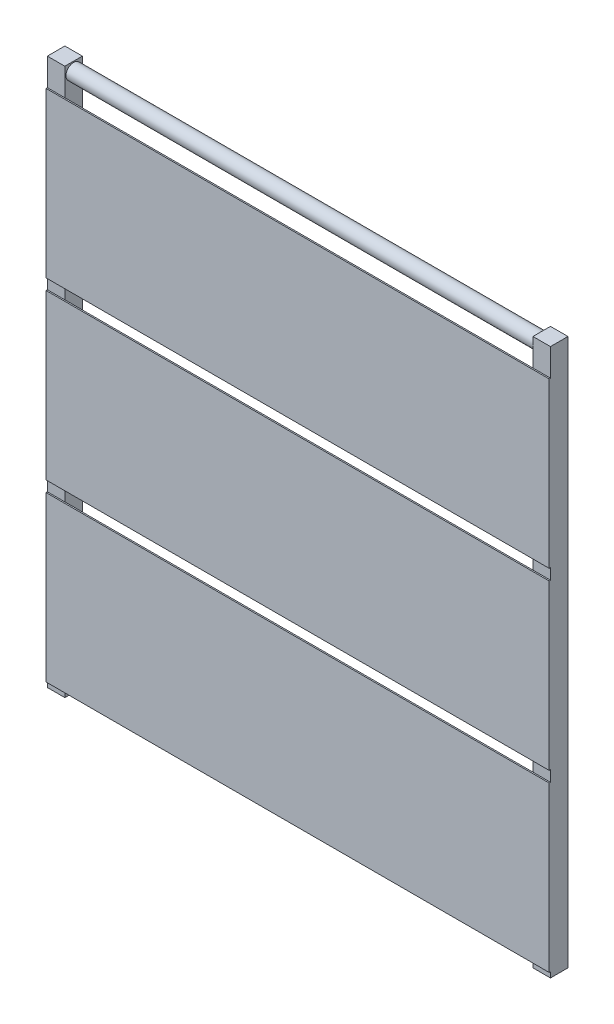
SolidWorks part; units mm, degrees
ref_plane "Front Plane" through (0, 0, 0) normal (0, 0, 1) x (1, 0, 0)
ref_plane "Top Plane" through (0, 0, 0) normal (0, 1, 0) x (1, 0, 0)
ref_plane "Right Plane" through (0, 0, 0) normal (1, 0, 0) x (0, 0, -1)
sketch "Sketch1" plane through (0, 0, 0) normal (0, 1, 0) x (1, 0, 0)
  line L0 (0, 213.1993) -> (0, -223.9488) construction
  line L1 (-230, -9.7) -> (-214, -9.7)
  line L2 (-230, -9.7) -> (-230, 6.3)
  line L3 (-230, 6.3) -> (-214, 6.3)
  line L4 (-214, -9.7) -> (-214, 6.3)
  line L5 (-230, -9.7) -> (-214, 6.3) construction
  line L6 (-230, 6.3) -> (-214, -9.7) construction
  line L7 (230, 6.3) -> (214, -9.7) construction
  line L8 (230, -9.7) -> (214, 6.3) construction
  line L9 (214, -9.7) -> (214, 6.3)
  line L10 (230, 6.3) -> (214, 6.3)
  line L11 (230, -9.7) -> (230, 6.3)
  line L12 (230, -9.7) -> (214, -9.7)
  point P0 (-222, -1.7)
  point P5 (-230, -1.7)
  point P13 (222, -1.7)
  dimension "D1" = 16
  dimension "D2" = 16
  dimension "D3" = 230
extrude "Boss-Extrude1" add sketch "Sketch1" along normal mid plane 500
sketch "Sketch2" plane through (0, 0, 9.7) normal (0, 0, 1) x (1, 0, 0)
  line L0 (230, 250) -> (230, -250) construction
  line L1 (-230, 225) -> (230, 225)
  line L2 (-230, 225) -> (-230, 75)
  line L3 (-230, 75) -> (230, 75)
  line L4 (230, 225) -> (230, 75)
  line L5 (-230, 225) -> (230, 75) construction
  line L6 (-230, 75) -> (230, 225) construction
  line L7 (-230, 250) -> (-214, 250) construction
  line L8 (-230, 65) -> (-230, -85)
  line L9 (-230, 65) -> (230, 65)
  line L10 (230, 65) -> (230, -85)
  line L11 (-230, -85) -> (230, -85)
  line L12 (-230, -95) -> (-230, -245)
  line L13 (-230, -95) -> (230, -95)
  line L14 (230, -95) -> (230, -245)
  line L15 (-230, -245) -> (230, -245)
  point P0 (0, 150)
  dimension "D1" = 25
  dimension "D2" = 460
  dimension "D3" = 150
  dimension "D4" = 3
extrude "Boss-Extrude2" add sketch "Sketch2" along normal blind 1.2
sketch "Sketch3" plane through (-214, 0, 0) normal (1, 0, 0) x (0, 0, -1)
  line L0 (-9.7, 250) -> (6.3, 250) construction
  circle A0 centre (-1.7, 242) radius 7
  dimension "D1" = 14
  dimension "D2" = 8
extrude "Boss-Extrude3" add sketch "Sketch3" along normal up to surface (428 mm away) up to face at (214, -6, 6.5)
